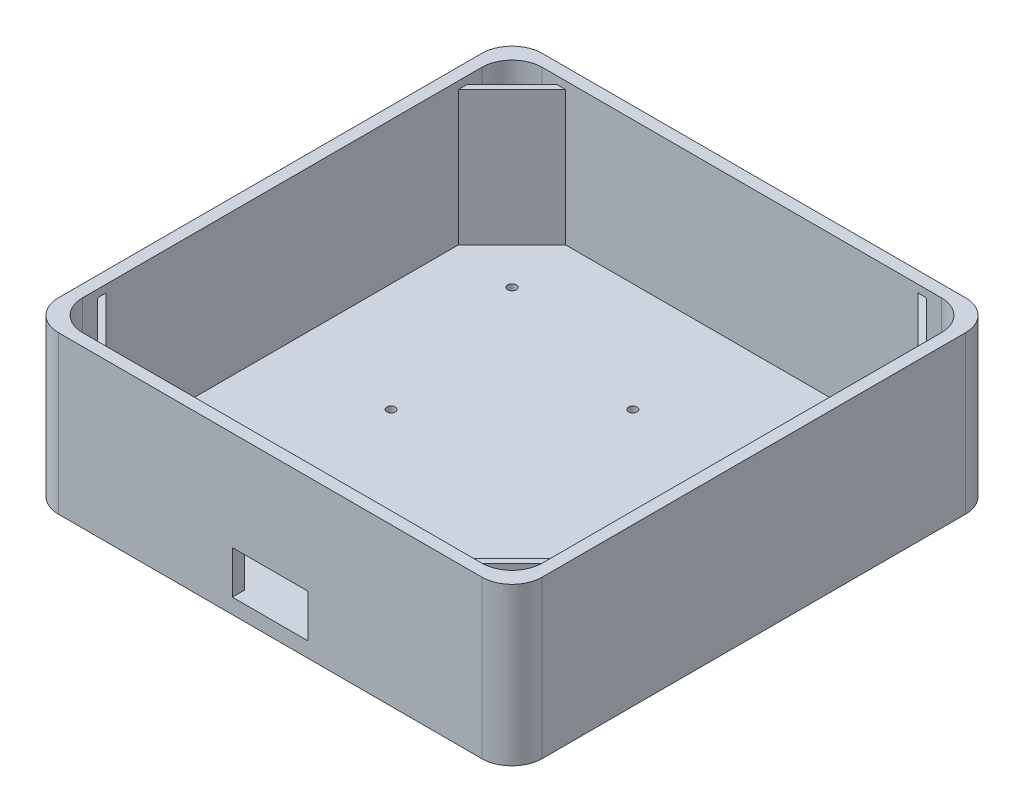
SolidWorks part; units mm, degrees
ref_plane "Front Plane" through (0, 0, 0) normal (0, 0, 1) x (1, 0, 0)
ref_plane "Top Plane" through (0, 0, 0) normal (0, 1, 0) x (1, 0, 0)
ref_plane "Right Plane" through (0, 0, 0) normal (1, 0, 0) x (0, 0, -1)
sketch "Sketch1" plane through (0, 0, 0) normal (0, 1, 0) x (1, 0, 0)
  line L0 (-76, 61.1508) -> (-61.1508, 76)
  line L1 (-80, -80) -> (80, -80)
  line L2 (-80, -80) -> (-80, 80)
  line L3 (-80, 80) -> (80, 80)
  line L4 (80, -80) -> (80, 80)
  line L5 (-80, -80) -> (80, 80) construction
  line L6 (-80, 80) -> (80, -80) construction
  line L7 (-76, -76) -> (76, -76)
  line L8 (-76, -76) -> (-76, 76)
  line L9 (-76, 76) -> (76, 76)
  line L10 (76, -76) -> (76, 76)
  line L11 (-76, -76) -> (76, 76) construction
  line L12 (-76, 76) -> (76, -76) construction
  line L13 (-76, 58.3223) -> (-58.3223, 76)
  line L14 (-110.7019, 0) -> (125.2362, 0) construction
  line L15 (0, 97.5375) -> (0, -67.8082) construction
  line L16 (76, 58.3223) -> (58.3223, 76)
  line L17 (76, 61.1508) -> (61.1508, 76)
  line L18 (76, -61.1508) -> (61.1508, -76)
  line L19 (76, -58.3223) -> (58.3223, -76)
  line L20 (-76, -58.3223) -> (-58.3223, -76)
  line L21 (-76, -61.1508) -> (-61.1508, -76)
  point P0 (0, 0)
  point P6 (0, 0)
  dimension "D1" = 160
  dimension "D2" = 160
  dimension "D3" = 4
  dimension "D4" = 4
  dimension "D5" = 21
  dimension "D6" = 25
  dimension "D7" = 45
  dimension "D8" = 45
extrude "Boss-Extrude1" add sketch "Sketch1" along normal blind 52 contours L1 L4 L3 L2 L10 L7 L8 L9 | L8 L13 L9 L0 | L8 L21 L7 L20 | L10 L19 L7 L18 | L10 L17 L9 L16
sketch "Sketch2" plane through (0, 0, 0) normal (0, 1, 0) x (1, 0, 0)
  line L1 (-80, -80) -> (80, -80)
  line L2 (-80, -80) -> (-80, 80)
  line L3 (-80, 80) -> (80, 80)
  line L4 (80, -80) -> (80, 80)
  line L5 (-80, -80) -> (80, 80) construction
  line L6 (-80, 80) -> (80, -80) construction
  point P0 (0, 0)
extrude "Boss-Extrude2" add sketch "Sketch2" along normal blind 5
sketch "Sketch3" plane through (0, 5, 0) normal (0, 1, 0) x (1, 0, 0)
  line L0 (0, 67.9803) -> (0, -47.0863) construction
  line L1 (53.5784, 0) -> (-59.2496, 0) construction
  circle A0 centre (-55, 55) radius 1.42
  circle A1 centre (55, 55) radius 1.42
  circle A2 centre (55, -55) radius 1.42
  circle A3 centre (-55, -55) radius 1.42
  circle A4 centre (0, 40) radius 1.42
  circle A5 centre (40, 0) radius 1.42
  circle A6 centre (0, -40) radius 1.42
  circle A7 centre (-40, 0) radius 1.42
  point P24 (0, 0)
  dimension "D1" = 2.84
  dimension "D5" = 2.84
  dimension "D2" = 55
  dimension "D3" = 55
  dimension "D4" = 40
  dimension "D6" = 4
extrude "Cut-Extrude1" cut sketch "Sketch3" against normal blind 10
sketch "Sketch4" plane through (0, 52, 0) normal (0, 1, 0) x (1, 0, 0)
  line L1 (-76, -76) -> (76, -76)
  line L2 (-76, -76) -> (-76, 76)
  line L3 (-76, 76) -> (76, 76)
  line L4 (76, -76) -> (76, 76)
  line L5 (-76, -76) -> (76, 76) construction
  line L6 (-76, 76) -> (76, -76) construction
  point P0 (0, 0)
extrude "Cut-Extrude2" cut sketch "Sketch4" against normal blind 2.5
fillet "Fillet1" radius 10 4 edges at (-80, 26, -80) (80, 26, -80) (80, 26, 80) (-80, 26, 80)
fillet "Fillet2" radius 10 4 edges at (76, 28.5, 76) (76, 28.5, -76) (-76, 28.5, 76) (-76, 28.5, -76)
sketch "Sketch5" plane through (0, 0, 0) normal (0, -1, 0) x (1, 0, 0)
  circle A0 centre (-55, 55) radius 3
  circle A1 centre (55, 55) radius 3
  circle A2 centre (55, -55) radius 3
  circle A3 centre (-55, -55) radius 3
  circle A4 centre (0, 40) radius 3
  circle A5 centre (-40, 0) radius 3
  circle A6 centre (0, -40) radius 3
  circle A7 centre (40, 0) radius 3
  dimension "D1" = 6
  dimension "D2" = 6
  dimension "D3" = 6
  dimension "D4" = 6
  dimension "D5" = 6
  dimension "D6" = 6
  dimension "D7" = 6
  dimension "D8" = 6
extrude "Cut-Extrude3" cut sketch "Sketch5" against normal blind 2
sketch "Sketch7" plane through (0, 0, 80) normal (0, 0, 1) x (1, 0, 0)
  line L1 (-12.5, 19.2096) -> (12.5, 19.2096)
  line L3 (-12.5, 19.2096) -> (-12.5, 5)
  line L4 (-12.5, 5) -> (12.5, 5)
  line L5 (12.5, 19.2096) -> (12.5, 5)
  line L8 (-70, 52) -> (-70, 0) construction
  dimension "D1" = 25
  dimension "D2" = 57.5
extrude "Cut-Extrude4" cut sketch "Sketch7" against normal blind 10
